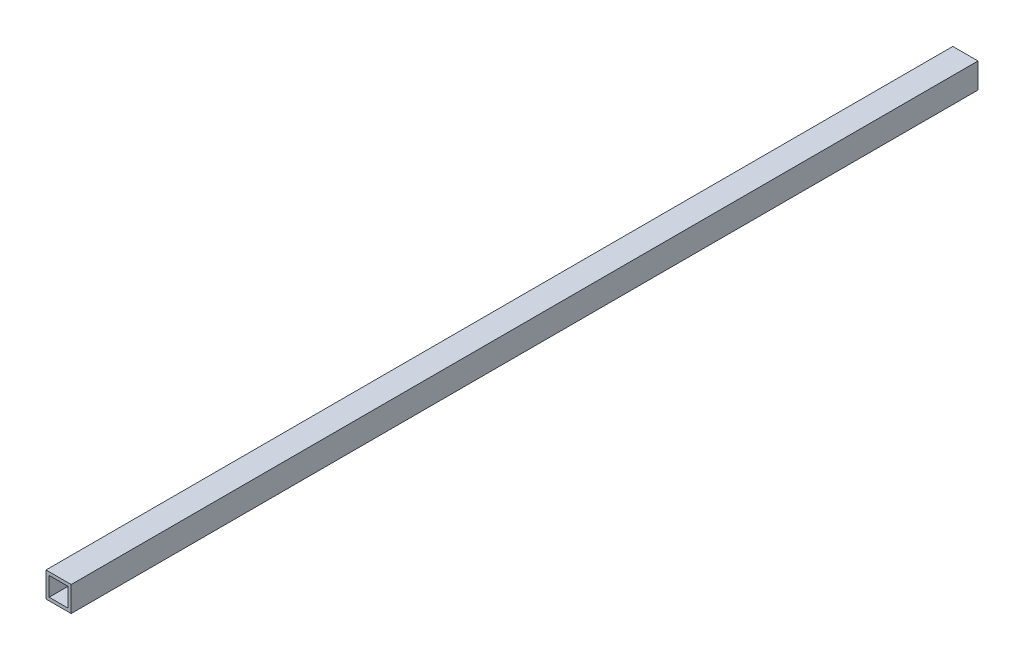
SolidWorks part; units mm, degrees
material "AISI 1020"
ref_plane "Front Plane" through (0, 0, 0) normal (0, 0, 1) x (1, 0, 0)
ref_plane "Top Plane" through (0, 0, 0) normal (0, 1, 0) x (1, 0, 0)
ref_plane "Right Plane" through (0, 0, 0) normal (1, 0, 0) x (0, 0, -1)
sketch "Sketch1" plane through (0, 0, 0) normal (0, 0, 1) x (1, 0, 0)
  line L0 (19.05, 19.05) -> (19.05, 25.4) construction
  line L1 (-25.4, -25.4) -> (25.4, -25.4)
  line L2 (-25.4, -25.4) -> (-25.4, 25.4)
  line L3 (-25.4, 25.4) -> (25.4, 25.4)
  line L4 (25.4, -25.4) -> (25.4, 25.4)
  line L5 (-25.4, -25.4) -> (25.4, 25.4) construction
  line L6 (-25.4, 25.4) -> (25.4, -25.4) construction
  line L7 (-19.05, -19.05) -> (19.05, -19.05)
  line L8 (-19.05, -19.05) -> (-19.05, 19.05)
  line L9 (-19.05, 19.05) -> (19.05, 19.05)
  line L10 (19.05, -19.05) -> (19.05, 19.05)
  line L11 (-19.05, -19.05) -> (19.05, 19.05) construction
  line L12 (-19.05, 19.05) -> (19.05, -19.05) construction
  line L13 (19.05, -19.05) -> (25.4, -19.05) construction
  point P0 (0, 0)
  point P6 (0, 0)
  dimension "D2" = 50.8
  dimension "D3" = 6.35
extrude "Boss-Extrude1" add sketch "Sketch1" along normal blind 1828.8
